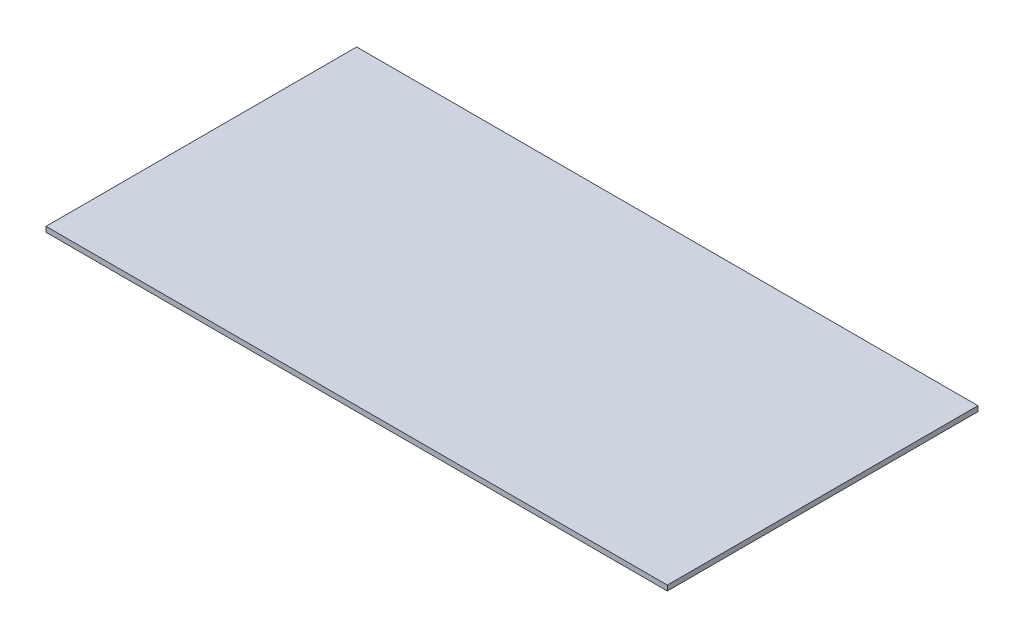
SolidWorks part; units mm, degrees
ref_plane "Front Plane" through (0, 0, 0) normal (0, 0, 1) x (1, 0, 0)
ref_plane "Top Plane" through (0, 0, 0) normal (0, 1, 0) x (1, 0, 0)
ref_plane "Right Plane" through (0, 0, 0) normal (1, 0, 0) x (0, 0, -1)
sketch "Sketch1" plane through (0, 0, 0) normal (0, 1, 0) x (1, 0, 0)
  line L1 (-152.4, -76.2) -> (152.4, -76.2)
  line L2 (-152.4, -76.2) -> (-152.4, 76.2)
  line L3 (-152.4, 76.2) -> (152.4, 76.2)
  line L4 (152.4, -76.2) -> (152.4, 76.2)
  line L5 (-152.4, -76.2) -> (152.4, 76.2) construction
  line L6 (-152.4, 76.2) -> (152.4, -76.2) construction
  point P0 (0, 0)
extrude "Boss-Extrude1" add sketch "Sketch1" along normal blind 2.54
